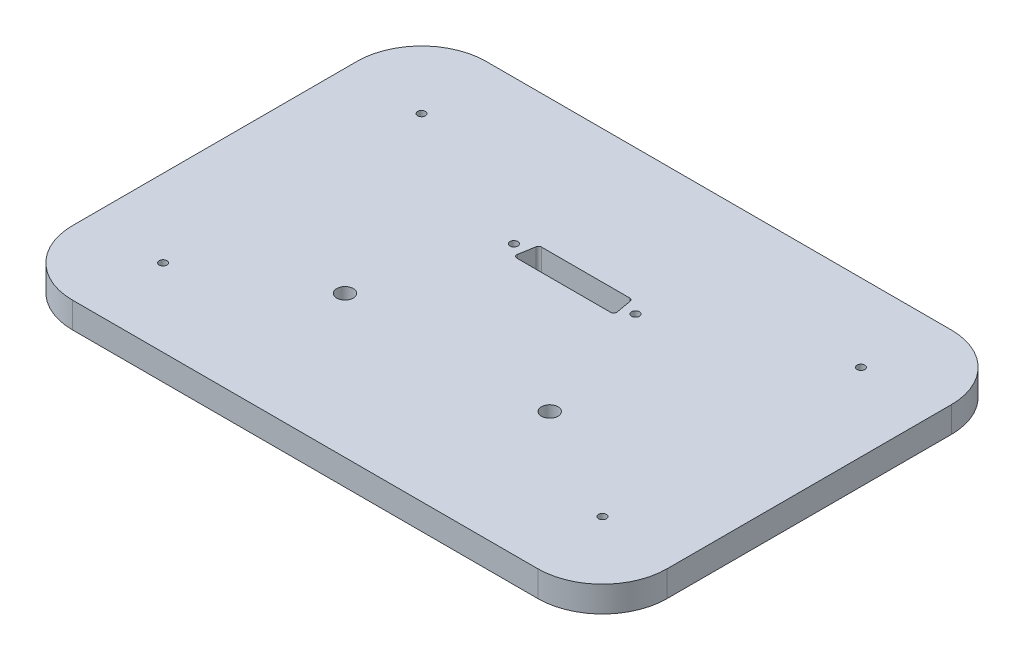
SolidWorks part; units mm, degrees
ref_plane "Front Plane" through (0, 0, 0) normal (0, 0, 1) x (1, 0, 0)
ref_plane "Top Plane" through (0, 0, 0) normal (0, 1, 0) x (1, 0, 0)
ref_plane "Right Plane" through (0, 0, 0) normal (1, 0, 0) x (0, 0, -1)
sketch "Sketch1" plane through (0, 0, 0) normal (0, 1, 0) x (1, 0, 0)
  line L1 (-90, -80) -> (90, -80)
  line L2 (-115, -55) -> (-115, 55)
  line L3 (-90, 80) -> (90, 80)
  line L4 (115, -55) -> (115, 55)
  line L5 (-115, -80) -> (115, 80) construction
  line L6 (-115, 80) -> (115, -80) construction
  arc A0 (-90, -80) -> (-115, -55) centre (-90, -55) cw
  arc A1 (90, -80) -> (115, -55) centre (90, -55) ccw
  arc A2 (90, 80) -> (115, 55) centre (90, 55) cw
  arc A3 (-115, 55) -> (-90, 80) centre (-90, 55) cw
  point P0 (0, 0)
  dimension "D3" = 25
  dimension "D1" = 230
  dimension "D2" = 160
extrude "Boss-Extrude1" add sketch "Sketch1" along normal blind 10
sketch "Sketch3" plane through (0, 10, 0) normal (0, 1, 0) x (1, 0, 0)
  line L0 (0, 80) -> (0, -80) construction
  line L1 (90, 80) -> (-90, 80) construction
  line L2 (-90, -80) -> (90, -80) construction
  line L3 (-83.5, 50) -> (0, 50) construction
  line L4 (83.5, 50) -> (0, 50) construction
  line L5 (-115, 0) -> (115, 0) construction
  line L6 (-115, 55) -> (-115, -55) construction
  line L7 (115, -55) -> (115, 55) construction
  line L8 (-85, 48.5) -> (-85, 0) construction
  line L9 (-85, 0) -> (-85, -48.5) construction
  circle A0 centre (-85, 50) radius 1.5
  circle A1 centre (85, 50) radius 1.5
  circle A2 centre (85, -50) radius 1.5
  circle A3 centre (-85, -50) radius 1.5
  dimension "D3" = 3
  dimension "D1" = 170
  dimension "D2" = 100
extrude "Cut-Extrude1" cut sketch "Sketch3" against normal blind 10
sketch "Sketch5" plane through (0, 0, 0) normal (0, -1, 0) x (1, 0, 0)
  line L0 (19.55, -20) -> (18.0512, -28.5)
  line L1 (-19.55, -20) -> (19.55, -20)
  line L3 (-18.0512, -28.5) -> (18.0512, -28.5)
  line L5 (-23.52, -24.25) -> (23.52, -24.25) construction
  line L6 (36.3982, 25) -> (0, 25) construction
  line L7 (-19.55, -20) -> (-18.0512, -28.5)
  line L8 (-19.55, 20.0928) -> (-19.55, 5.6432) construction
  line L9 (19.55, -3.793) -> (19.55, -14.9781) construction
  line L10 (0, 80) -> (0, -80) construction
  line L11 (-90, 80) -> (90, 80) construction
  line L12 (90, -80) -> (-90, -80) construction
  line L13 (0, 25) -> (-36.3982, 25) construction
  circle A0 centre (23.52, -24.25) radius 1.525
  circle A1 centre (-23.52, -24.25) radius 1.525
  circle A2 centre (-39.5982, 25) radius 3.2
  circle A3 centre (39.5982, 25) radius 3.2
  point P9 (0, -20)
  point P19 (0, -24.25)
  point P22 (-18.8006, -24.25)
  dimension "D6" = 3.05
  dimension "D8" = 6.4
  dimension "D9" = 6.4
  dimension "D1" = 39.1
  dimension "D2" = 10
  dimension "D3" = 10
  dimension "D4" = 8.5
  dimension "D5" = 60
  dimension "D7" = 47.04
  dimension "D10" = 55
extrude "Cut-Extrude2" cut sketch "Sketch5" against normal blind 10
fillet "Fillet1" radius 1.2 4 edges at (-18.0512, 5, -28.5) (-19.55, 5, -20) (18.0512, 5, -28.5) (19.55, 5, -20)
sketch "Sketch7" plane through (0, 0, 0) normal (0, -1, 0) x (1, 0, 0)
  line L0 (-85, 65) -> (85, 65)
  line L1 (100, 50) -> (100, -50)
  line L2 (85, -65) -> (-85, -65)
  line L3 (-100, -50) -> (-100, 50)
  line L4 (-90, 80) -> (90, 80) construction
  line L5 (115, 55) -> (115, -55) construction
  line L6 (90, -80) -> (-90, -80) construction
  line L7 (-115, -55) -> (-115, 55) construction
  arc A0 (-85, -65) -> (-100, -50) centre (-85, -50) cw
  arc A1 (100, -50) -> (85, -65) centre (85, -50) cw
  arc A2 (85, 65) -> (100, 50) centre (85, 50) cw
  arc A3 (-85, 65) -> (-100, 50) centre (-85, 50) ccw
  dimension "D5" = 15
  dimension "D1" = 15
  dimension "D2" = 15
  dimension "D3" = 15
  dimension "D4" = 15
extrude "Cut-Extrude-Thin1" cut sketch "Sketch7" against normal blind 5 thin thin type mid plane wall 5
